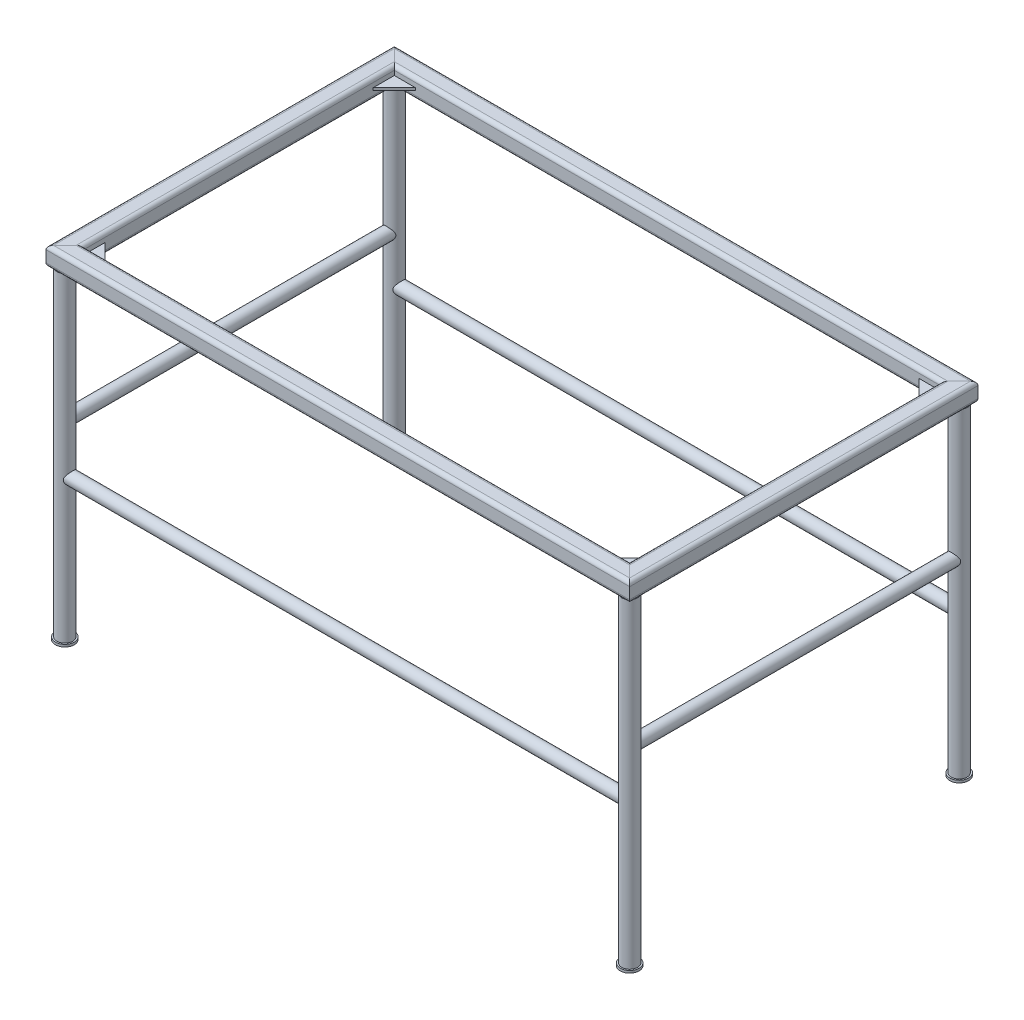
SolidWorks part; units mm, degrees
other "DetailItem2"
other "DetailItem3"
other "DetailItem4"
other "DetailItem5"
other "DetailItem6"
other "DetailItem7"
other "DetailItem8"
other "DetailItem9"
other "DetailItem10"
other "DetailItem11"
other "DetailItem12"
other "DetailItem13"
other "DetailItem14"
other "DetailItem15"
other "DetailItem16"
other "DetailItem17"
other "DetailItem18"
other "DetailItem19"
other "Weld Folder"
other "Weld Bead2"
other "Weld Bead3"
other "Weld Bead4"
other "Weld Bead5"
other "Weld Bead6"
other "Weld Bead7"
other "Weld Bead8"
other "Weld Bead9"
other "Weld Bead10"
other "Weld Bead11"
other "Weld Bead12"
other "Weld Bead13"
other "Weld Bead14"
other "Weld Bead15"
other "Weld Bead16"
other "Weld Bead17"
other "Weld Bead18"
other "Weld Bead19"
ref_plane "Płaszczyzna przednia" through (0, 0, 0) normal (0, 0, 1) x (1, 0, 0)
ref_plane "Płaszczyzna górna" through (0, 0, 0) normal (0, 1, 0) x (1, 0, 0)
ref_plane "Płaszczyzna prawa" through (0, 0, 0) normal (1, 0, 0) x (0, 0, -1)
sketch3d "3DSketch1"
  line L0 (-600, 0, 350) -> (-600, -700, 350)
  line L1 (-600, 0, 350) -> (-600, 0, -350)
  line L2 (-600, 0, 350) -> (600, 0, 350)
  line L3 (600, 0, 350) -> (600, 0, -350)
  line L4 (-600, 0, -350) -> (600, 0, -350)
  line L5 (-600, 0, 350) -> (600, 0, -350) construction
  line L6 (600, 0, 350) -> (-600, 0, -350) construction
  line L7 (600, 0, 350) -> (600, -700, 350)
  line L8 (600, 0, -350) -> (600, -700, -350)
  line L9 (-600, 0, -350) -> (-600, -700, -350)
  line L10 (-600, -400, 350) -> (600, -400, 350)
  line L11 (-600, -400, -350) -> (600, -400, -350)
  line L12 (-600, -300, 350) -> (-600, -300, -350)
  line L13 (600, -300, 350) -> (600, -300, -350)
  point P0 (0, 0, 0)
  dimension "D1" = 700
  dimension "D2" = 1200
  dimension "D3" = 700
  dimension "D4" = 300
  dimension "D5" = 300
  dimension "D6" = 400
  dimension "D7" = 400
other "Square tube 40 X 40 X 4(1)"
ref_plane "Plane1" through (-600, 0, 350) normal (1, 0, 0) x (0, 0, -1)
sketch "Sketch1" plane through (-600, 0, 350) normal (1, 0, 0) x (0, 0, -1)
  line L0 (-12, -16) -> (12, -16)
  line L1 (-16, -12) -> (-16, 12)
  line L2 (12, 16) -> (-12, 16)
  line L3 (16, 12) -> (16, -12)
  line L4 (-12, -20) -> (12, -20)
  line L5 (-20, -12) -> (-20, 12)
  line L6 (12, 20) -> (-12, 20)
  line L7 (20, 12) -> (20, -12)
  arc A0 (20, 12) -> (12, 20) centre (12, 12) ccw
  arc A1 (12, -20) -> (20, -12) centre (12, -12) ccw
  arc A2 (-20, -12) -> (-12, -20) centre (-12, -12) ccw
  arc A3 (-12, 20) -> (-20, 12) centre (-12, 12) ccw
  arc A4 (-12, 16) -> (-16, 12) centre (-12, 12) ccw
  arc A5 (16, 12) -> (12, 16) centre (12, 12) ccw
  arc A6 (12, -16) -> (16, -12) centre (12, -12) ccw
  arc A7 (-16, -12) -> (-12, -16) centre (-12, -12) ccw
  point P0 (-20, 0)
  point P1 (20, 0)
  point P2 (0, 20)
  point P3 (0, -20)
  point P4 (0, 0)
  point P5 (-20, -20)
  point P6 (20, -20)
  point P7 (20, 20)
  point P8 (-20, 20)
  point P33 (0, 0)
  dimension "D1" = 8
  dimension "Thickness" = 4
  dimension "V_leg" = 40
other "Pipe 33.7 X 4.0(1)"
ref_plane "Plane2" through (-600, 0, 350) normal (0, -1, 0) x (1, 0, 0)
sketch "Sketch11" plane through (-600, 0, 350) normal (0, -1, 0) x (1, 0, 0)
  circle A0 centre (0, 0) radius 12.85
  circle A1 centre (0, 0) radius 16.85
  point P3 (0, 0)
  dimension "In_dia" = 25.7
  dimension "Out_dia" = 33.7
other "Pipe 26.9 X 3.2(2)"
ref_plane "Plane4" through (-600, -400, 350) normal (1, 0, 0) x (0, 0, -1)
sketch "Sketch13" plane through (-600, -400, 350) normal (1, 0, 0) x (0, 0, -1)
  circle A0 centre (0, 0) radius 10.25
  circle A1 centre (0, 0) radius 13.45
  point P3 (0, 0)
  dimension "In_dia" = 20.5
  dimension "Out_dia" = 26.9
other "Pipe 26.9 X 3.2(3)"
ref_plane "Plane5" through (-600, -300, 350) normal (0, 0, -1) x (1, 0, 0)
sketch "Sketch14" plane through (-600, -300, 350) normal (0, 0, -1) x (1, 0, 0)
  circle A0 centre (0, 0) radius 10.25
  circle A1 centre (0, 0) radius 13.45
  point P3 (0, 0)
  dimension "In_dia" = 20.5
  dimension "Out_dia" = 26.9
other "Gusset1" parameters "D1"=5, "D2"=5, "D3"=0, "D4"=0, "D10"=5, "D11"=45, "D12"=45, "D13"=15, "D14"=45, "D15"=15
sketch "Sketch15" plane through (-580, 0, 330) normal (0, 1, 0) x (1, 0, 0)
  line L0 (0, 0) -> (45, 0)
  line L1 (0, 0) -> (0, 45)
  line L2 (45, 0) -> (0, 45)
other "Trim/Extend1"
other "Trim/Extend2"
other "Gusset2" parameters "D1"=5, "D2"=5, "D3"=0, "D4"=0, "D10"=5, "D11"=45, "D12"=45, "D13"=15, "D14"=45, "D15"=15
sketch "Sketch16" plane through (-580, 0, -330) normal (0, 1, 0) x (1, 0, 0)
  line L0 (0, 0) -> (0, -45)
  line L1 (0, 0) -> (45, 0)
  line L2 (0, -45) -> (45, 0)
other "Gusset3" parameters "D1"=5, "D2"=5, "D3"=0, "D4"=0, "D10"=5, "D11"=45, "D12"=45, "D13"=15, "D14"=45, "D15"=15
sketch "Sketch17" plane through (580, 0, 330) normal (0, -1, 0) x (-1, 0, 0)
  line L0 (0, 0) -> (45, 0)
  line L1 (0, 0) -> (0, 45)
  line L2 (45, 0) -> (0, 45)
other "Gusset4" parameters "D1"=5, "D2"=5, "D3"=0, "D4"=0, "D10"=5, "D11"=45, "D12"=45, "D13"=15, "D14"=45, "D15"=15
sketch "Sketch18" plane through (580, 0, -330) normal (0, -1, 0) x (-1, 0, 0)
  line L0 (0, 0) -> (0, -45)
  line L1 (0, 0) -> (45, 0)
  line L2 (0, -45) -> (45, 0)
sketch "Sketch19" plane through (0, -700, 0) normal (0, -1, 0) x (1, 0, 0)
  circle A0 centre (-600, -350) radius 20
  dimension "D1" = 40
extrude "Boss-Extrude1" add sketch "Sketch19" along normal blind 5 separate body
pattern_linear "LPattern1" count 2 spacing 700 along (0, 0, 1) of "Boss-Extrude1"
pattern_linear "LPattern2" count 2 spacing 1200 along (1, 0, 0) of "Boss-Extrude1"
sketch "Sketch20" plane through (0, -700, 0) normal (0, -1, 0) x (1, 0, 0)
  circle A0 centre (600, 350) radius 20
  dimension "D1" = 40
extrude "Boss-Extrude2" add sketch "Sketch20" along normal blind 5 separate body
